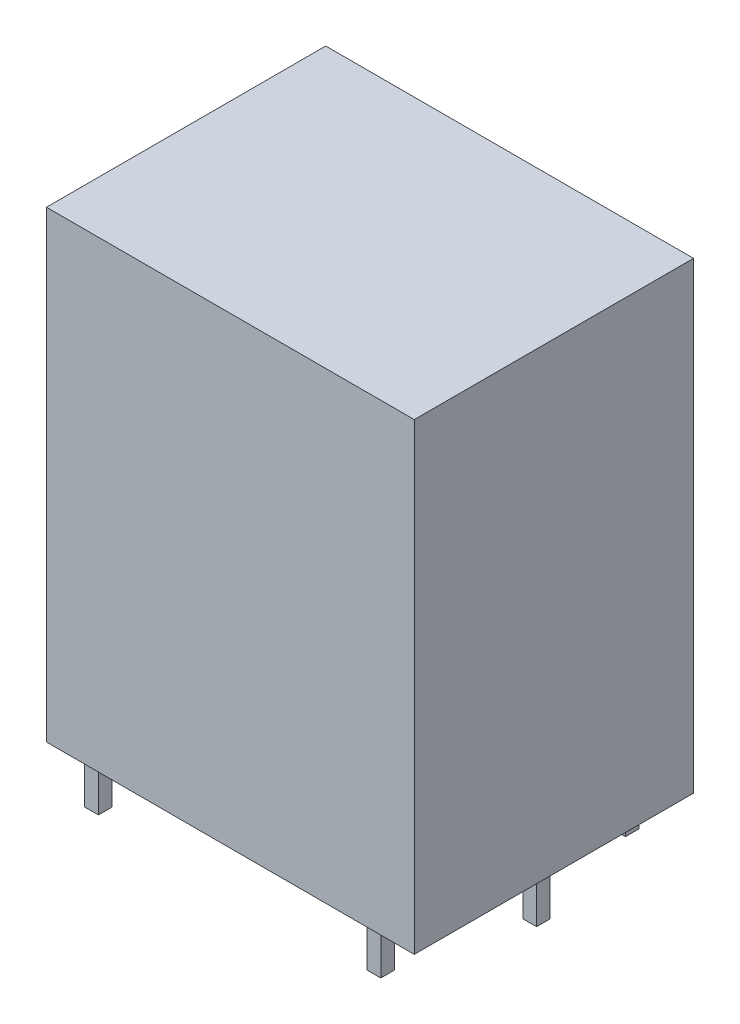
SolidWorks part; units mm, degrees
ref_plane "前视基准面" through (0, 0, 0) normal (0, 0, 1) x (1, 0, 0)
ref_plane "上视基准面" through (0, 0, 0) normal (0, 1, 0) x (1, 0, 0)
ref_plane "右视基准面" through (0, 0, 0) normal (1, 0, 0) x (0, 0, -1)
sketch "草图1" plane through (0, 0, 0) normal (0, 1, 0) x (1, 0, 0)
  line L0 (0, 41.7773) -> (0, -45.7415) construction
  line L1 (-13.5, 10.25) -> (13.5, 10.25)
  line L2 (-13.5, 10.25) -> (-13.5, -10.25)
  line L3 (-13.5, -10.25) -> (13.5, -10.25)
  line L4 (13.5, 10.25) -> (13.5, -10.25)
  line L5 (-48.486, 0) -> (58.5492, 0) construction
  dimension "D1" = 27
  dimension "D2" = 20.5
extrude "拉伸1" add sketch "草图1" along normal blind 34
sketch "草图2" plane through (0, 0, 0) normal (0, -1, 0) x (1, 0, 0)
  line L0 (9.9294, 0) -> (-10.2276, 0) construction
  line L1 (12.73, -0.5) -> (11.73, -0.5)
  line L2 (12.73, -0.5) -> (12.73, 0.5)
  line L3 (12.73, 0.5) -> (11.73, 0.5)
  line L4 (11.73, -0.5) -> (11.73, 0.5)
  line L5 (12.23, -1.6251) -> (12.23, 1.1288) construction
  line L6 (13.5, 10.25) -> (13.5, -10.25) construction
  line L7 (8.0786, 8.98) -> (-8.6507, 8.98) construction
  line L8 (10.27, 9.48) -> (9.27, 9.48)
  line L9 (10.27, 9.48) -> (10.27, 8.48)
  line L10 (10.27, 8.48) -> (9.27, 8.48)
  line L11 (9.27, 9.48) -> (9.27, 8.48)
  line L12 (-13.5, 10.25) -> (13.5, 10.25) construction
  line L13 (9.77, 4.8939) -> (9.77, 7.944) construction
  line L14 (-10.46, 9.48) -> (-11.46, 9.48)
  line L15 (-10.46, 9.48) -> (-10.46, 8.48)
  line L16 (-10.46, 8.48) -> (-11.46, 8.48)
  line L17 (-11.46, 9.48) -> (-11.46, 8.48)
  line L18 (-10.96, 7.128) -> (-10.96, 5.1977) construction
  line L19 (-13.5, -10.25) -> (-13.5, 10.25) construction
  line L20 (-11.46, -9.48) -> (-11.46, -8.48)
  line L21 (-10.46, -8.48) -> (-11.46, -8.48)
  line L22 (-10.46, -9.48) -> (-10.46, -8.48)
  line L23 (-10.46, -9.48) -> (-11.46, -9.48)
  line L24 (9.27, -9.48) -> (9.27, -8.48)
  line L25 (10.27, -8.48) -> (9.27, -8.48)
  line L26 (10.27, -9.48) -> (10.27, -8.48)
  line L27 (10.27, -9.48) -> (9.27, -9.48)
  dimension "D1" = 1
  dimension "D2" = 1
  dimension "D3" = 1.27
  dimension "D4" = 1
  dimension "D5" = 1
  dimension "D6" = 1.27
  dimension "D7" = 3.73
  dimension "D8" = 1
  dimension "D9" = 1
  dimension "D10" = 2.54
extrude "拉伸2" add sketch "草图2" along normal blind 3.5
